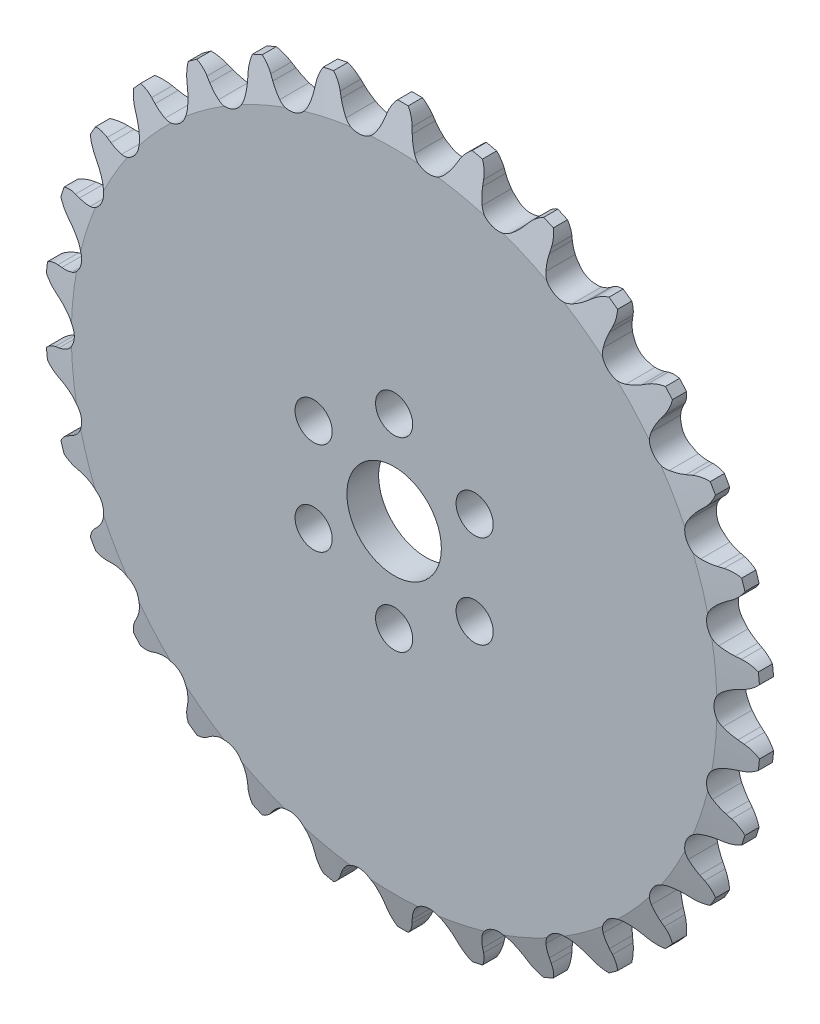
SolidWorks part; units mm, degrees
ref_plane "Front Plane" through (0, 0, 0) normal (0, 0, 1) x (1, 0, 0)
ref_plane "Top Plane" through (0, 0, 0) normal (0, 1, 0) x (1, 0, 0)
ref_plane "Right Plane" through (0, 0, 0) normal (1, 0, 0) x (0, 0, -1)
sketch "Sketch0" plane through (0, 0, 0) normal (0, 0, 1) x (1, 0, 0)
  line L0 (4.7625, -45.3122) -> (0, 0) construction
  line L1 (0, 0) -> (14.0794, -43.3318) construction
  line L2 (0, 0) -> (-4.7625, -45.3122) construction
  line L3 (4.7625, -45.3122) -> (14.0794, -43.3318) construction
  line L4 (4.7625, -45.3122) -> (-4.7625, -45.3122) construction
  line L5 (8.0084, -45.7133) -> (7.6941, -45.0929)
  line L6 (4.7625, -45.3122) -> (0, -45.8127) construction
  line L7 (1.6709, -46.3794) -> (1.8494, -45.7072)
  line L8 (0, -45.3122) -> (0, -48.1697) construction
  line L9 (6.6305, -43.5702) -> (1.7903, -48.0838) construction
  line L10 (0, 0) -> (0, -45.3122) construction
  line L11 (7.6941, -45.0929) -> (1.7903, -48.0838) construction
  line L12 (0, -48.1697) -> (0, -48.7448) construction
  line L13 (11.7191, -43.8335) -> (8.0084, -45.7133) construction
  circle A0 centre (0, 0) radius 48.1697 construction
  circle A1 centre (0, 0) radius 45.5618 construction
  arc A2 (-2.5649, -49.4663) -> (12.7935, -47.852) centre (0, 0) ccw
  circle A3 centre (0, 0) radius 48.7448 construction
  circle A4 centre (4.7625, -45.3122) radius 2.54 construction
  arc A7 (6.6305, -43.5702) -> (2.5731, -43.9967) centre (4.7625, -45.3122) ccw
  circle A8 centre (4.7625, -45.3122) radius 2.5542 construction
  arc A9 (8.0084, -45.7133) -> (12.7935, -47.852) centre (11.7191, -43.8335) ccw
  arc A10 (7.6941, -45.0929) -> (6.6305, -43.5702) centre (1.7903, -48.0838) ccw
  arc A11 (1.6709, -46.3794) -> (-2.5649, -49.4663) centre (-2.3495, -45.3122) cw
  arc A12 (1.8494, -45.7072) -> (2.5731, -43.9967) centre (8.246, -47.4053) cw
  dimension "D1" = 2.5542
  dimension "R" = 2.5542
sketch "Sketch1" plane through (0, 0, 0) normal (1, 0, 0) x (0, 0, -1)
  line L0 (2.1336, 0) -> (-2.1336, 0)
  line L1 (-2.1336, 0) -> (-2.1336, 43.4072)
  line L2 (-2.1336, 43.4072) -> (-0.943, 48.1697)
  line L3 (-0.943, 48.1697) -> (0.943, 48.1697)
  line L4 (0.943, 48.1697) -> (2.1336, 43.4072)
  line L5 (2.1336, 43.4072) -> (2.1336, 0)
  line L7 (0, 48.1697) -> (0, 0) construction
  line L8 (-2.1336, 43.4072) -> (2.1336, 43.4072) construction
  line L9 (0, 48.1697) -> (0, -48.1697) construction
  line L10 (-2.1336, 43.4072) -> (-2.1336, 48.1697) construction
  line L11 (-2.1336, 48.1697) -> (-0.943, 48.1697) construction
  line L12 (0.943, 48.1697) -> (2.1336, 48.1697) construction
  line L13 (2.1336, 48.1697) -> (2.1336, 43.4072) construction
revolve "Revolve1" add sketch "Sketch1" angle 360 mid plane about L0
extrude "Cut-Extrude1" cut sketch "Sketch0" against normal through all and the other way through all
pattern_circular "CirPattern1" count 30 over 360 about axis through (0, 0, 0) along (0, 0, 1) of "Cut-Extrude1"
sketch "Sketch2" plane through (0, 0, 0) normal (0, 0, 1) x (1, 0, 0)
  circle A0 centre (0, 0) radius 6.35 construction
  circle A1 centre (0, 0) radius 30.1625
  circle A2 centre (0, 0) radius 48.133 construction
  dimension "Bore" = 12.7
  dimension "Hub Dia." = 60.325
  dimension "OD" = 96.266
sketch "Sketch3" plane through (0, 0, 0) normal (0, 0, 1) x (1, 0, 0)
  circle A0 centre (0, 0) radius 6.35 construction
  circle A1 centre (0, 0) radius 6.35
  circle A2 centre (0, 0) radius 48.133 construction
  circle A3 centre (0, 0) radius 48.133
extrude "Cut-Extrude2" cut sketch "Sketch3" along normal through all and the other way through all flip side to cut
sketch "Sketch4" plane through (0, 0, 2.1336) normal (0, 0, 1) x (1, 0, 0)
  circle A0 centre (0, 0) radius 12.5 construction
  circle A2 centre (0, 0) radius 20 construction
  dimension "D1" = 25
  dimension "D2" = 40
hole_wizard "Tap Drill for M6x1.0 Tap1" positions "Sketch5" profile "Sketch6" hole size "M6x1.0" standard "ANSI Metric" end condition through all
sketch "Sketch5" plane through (0, 0, 2.1336) normal (0, 0, 1) x (1, 0, 0)
  circle A0 centre (0, 0) radius 12.5 construction
  point P0 (0, 12.5)
sketch "Sketch6" plane through (0, 12.5, 2.1336) normal (1, 0, 0) x (0, -1, 0)
  line L0 (0, 0) -> (0, 4.2672)
  line L1 (0, 4.2672) -> (2.5, 4.2672)
  line L2 (2.5, 4.2672) -> (2.5, 0)
  line L5 (2.5, 0) -> (0, 0)
  line L11 (0, -6.35) -> (0, 107.95) construction
  dimension "Thru Hole Dia." = 5
  dimension "Thru Hole Depth" = 4.2672
pattern_circular "CirPattern2" count 6 over 360 about axis through (0, 0, 0) along (0, 0, 1) of "Tap Drill for M6x1.0 Tap1"
equation "\"360/N@Sketch0\" = 360/\"Teeth@CirPattern1\""
equation "\"Ds@Sketch0\" = 1.005 * \"Dr@Sketch0\" + 0.003"
equation "\"R@Sketch0\" = 1/2 * \"Ds@Sketch0\""
equation "\"A@Sketch0\" = 35 +  ( 60 / \"Teeth@CirPattern1\" ) "
equation "\"B@Sketch0\" = 18 -  ( 56 / \"Teeth@CirPattern1\" )"
equation "\"ac@Sketch0\" = 0.8 * \"Dr@Sketch0\""
equation "\"ab@Sketch0\" = 1.4 * \"Dr@Sketch0\""
equation "\"J@Sketch0\" = 0.3 * \"Pitch@Sketch0\""
equation "\"h@Sketch1\" = \"Pitch@Sketch0\" / 2"
equation "\"g@Sketch1\" = \"h@Sketch1\" / 4"
